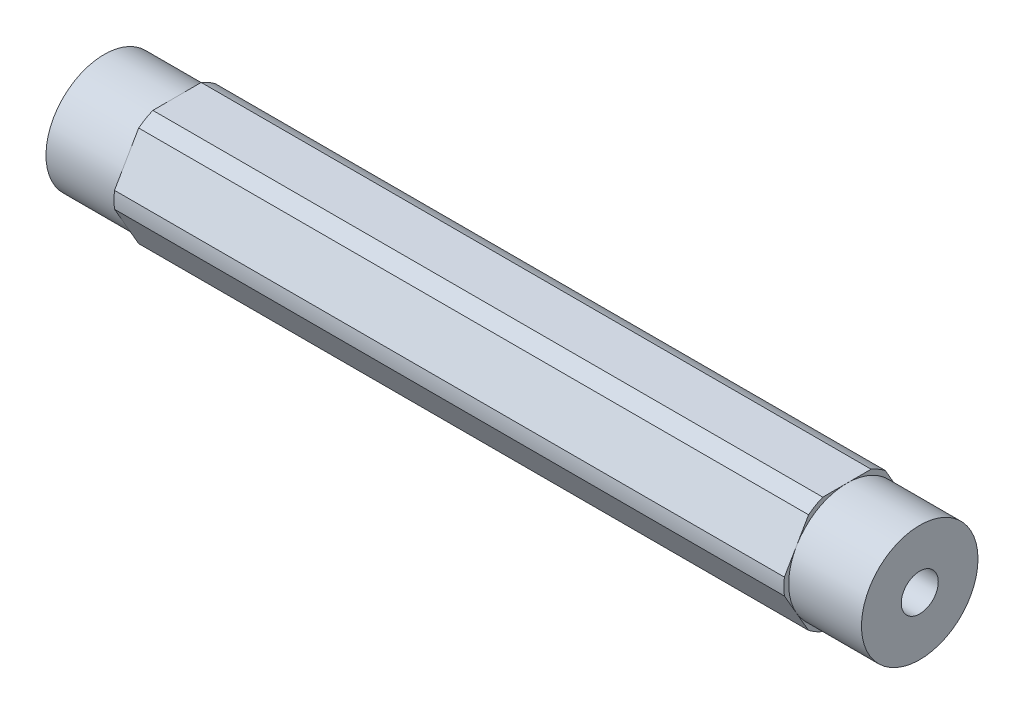
SolidWorks part; units mm, degrees
material "7075-T6 (SN)"
ref_plane "Front Plane" through (0, 0, 0) normal (0, 0, 1) x (1, 0, 0)
ref_plane "Top Plane" through (0, 0, 0) normal (0, 1, 0) x (1, 0, 0)
ref_plane "Right Plane" through (0, 0, 0) normal (1, 0, 0) x (0, 0, -1)
sketch "Sketch1" plane through (0, 0, 0) normal (1, 0, 0) x (0, 0, -1)
  line L1 (7.3323, 0) -> (3.6662, 6.35)
  line L2 (3.6662, 6.35) -> (-3.6662, 6.35)
  line L3 (-3.6662, 6.35) -> (-7.3323, 0)
  line L4 (-7.3323, 0) -> (-3.6662, -6.35)
  line L5 (-3.6662, -6.35) -> (3.6662, -6.35)
  line L6 (3.6662, -6.35) -> (7.3323, 0)
  circle A0 centre (0, 0) radius 6.875
  circle A1 centre (0, 0) radius 2.0193
  circle A2 centre (0, 0) radius 6.35 construction
  dimension "D1" = 12.7
  dimension "D2" = 13.75
  dimension "D3" = 4.0386
extrude "Boss-Extrude1" add sketch "Sketch1" along normal mid plane 88.9 contours L1 A0 L2 L3 L4 L5 L6 A1
sketch "Sketch2" plane through (44.45, 0, 0) normal (1, 0, 0) x (0, 0, -1)
  circle A0 centre (0, 0) radius 6.35
  dimension "D1" = 12.7
extrude "Cut-Extrude-Thin1" cut sketch "Sketch2" against normal blind 7.9375 thin
mirror "Mirror1" about plane through (0, 0, 0) normal (1, 0, 0) of "Cut-Extrude-Thin1"
equation "\"D2@Sketch1\"=13.75mm"
